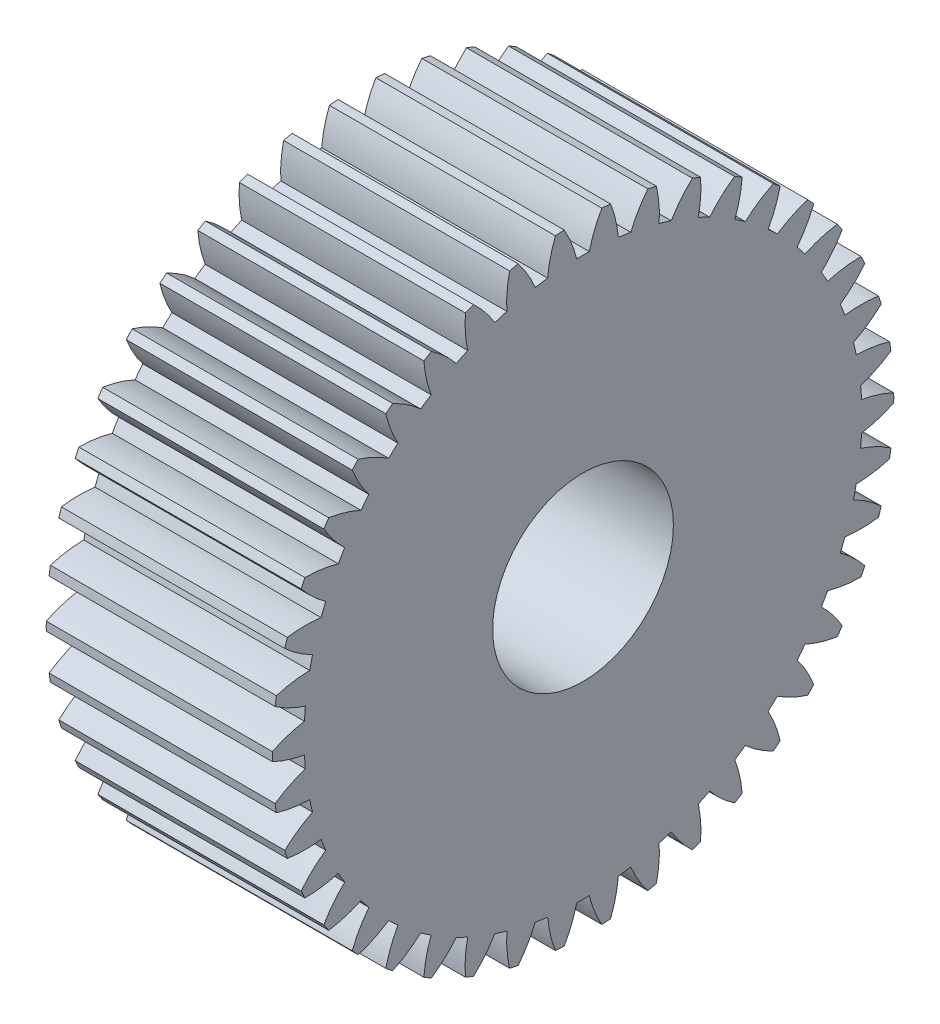
SolidWorks part; units mm, degrees
ref_plane "Plane1" through (0, 0, 0) normal (0, 0, 1) x (1, 0, 0)
ref_plane "Plane2" through (0, 0, 0) normal (0, 1, 0) x (1, 0, 0)
ref_plane "Plane3" through (0, 0, 0) normal (1, 0, 0) x (0, 0, -1)
sketch "HoldingSke" plane through (0, 0, 0) normal (0, 1, 0) x (1, 0, 0)
  line L0 (0, 0) -> (1.4863, -1.3383)
  line L1 (-15, 0) -> (100, 0) construction
  line L2 (0, 0) -> (-2.1039, 2.3779)
  line L3 (0, 0) -> (-11.863, 4.5341)
  line L4 (0, 0) -> (6.4178, 5.7786)
  line L5 (0, 0) -> (-46.8476, -17.4728)
  line L6 (0, 0) -> (-6.6317, -4.4744)
  line L7 (-2.1039, 2.3779) -> (8.6586, 51.2059)
  line L8 (-76.2, 54.61) -> (-75.9, 54.61)
  line L9 (-71.009, 38.7566) -> (-53.1078, 45.2721)
  line L10 (-76.2, 71.12) -> (104.1128, 71.12)
  line L11 (0, 0) -> (-8, 0)
  line L12 (-76.2, 101.6) -> (-76.181, 101.6)
  line L13 (24.9733, 27.94) -> (52.9518, 28.4284)
  line L14 (24.9733, 27.94) -> (24.9743, 27.94)
  line L15 (24.9733, 27.94) -> (100.4006, 29.5858)
  line L16 (-63.627, -0.5) -> (-12.827, -0.5)
  circle A0 centre (0, 0) radius 1
  circle A1 centre (0, 0) radius 9.874
  circle A2 centre (0, 0) radius 37.5
  circle A3 centre (0, 0) radius 1
  dimension "MHD" = 19.748
  dimension "Hub_dia" = 75
  dimension "Bore" = 2
  dimension "MBD" = 2
  dimension "Num_teeth" = 42
  dimension "Pitch" = 2
  dimension "Overall_len" = 50
  dimension "Show_teeth" = 42
  dimension "Thickness" = 8
  dimension "OAL" = 50.0001
  dimension "T_dim" = 0.3
  dimension "Ap" = 20
  dimension "H" = 19.05
  dimension "Pitch_radius" = 180.3128
  dimension "Width" = 8
  dimension "Backlash" = 0.019
  dimension "Addendum_fac" = 1
  dimension "Dedendum_fac" = 1.25
  dimension "Clearance_fac" = 0.25
  dimension "Dedendum_add" = 0.001
  dimension "Module" = 0.5
sketch "BasProSke" plane through (0, 0, 0) normal (0, 1, 0) x (1, 0, 0)
  line L0 (-10, 0) -> (60, 0) construction
  line L1 (0, 0) -> (0, 11)
  line L2 (0, 0) -> (8, 0)
  line L3 (8, 0) -> (8, 11)
  line L4 (8, 11) -> (0, 11)
  dimension "Thickness" = 8
  dimension "Diameter" = 22
revolve "Base-Revolve" add sketch "BasProSke" angle 360 about L0
sketch "TooCutSke" plane through (0, 0, 0) normal (1, 0, 0) x (0, 0, -1)
  line L1 (0, 0) -> (0, 107) construction
  line L2 (0, 0) -> (-0.4259, 10.4914) construction
  line L3 (0, 0) -> (-1.5684, 20.929) construction
  line L4 (-0.4259, 10.4914) -> (-0.7842, 10.4645) construction
  arc A0 (0.2229, 9.8715) -> (-0.2229, 9.8715) centre (0, 0) ccw
  arc A1 (0.6815, 11.0043) -> (-0.6815, 11.0043) centre (0, 0) ccw
  circle A2 centre (0, 0) radius 10.5 construction
  circle A3 centre (0, 0) radius 9.8668 construction
  arc A4 (-0.2229, 9.8715) -> (-0.6815, 11.0043) centre (-4.3039, 8.8786) ccw
  arc A5 (0.6815, 11.0043) -> (0.2229, 9.8715) centre (4.3039, 8.8786) ccw
  dimension "Root_dia" = 19.748
  dimension "Overcut_dia" = 22.0508
  dimension "Pitch_dia" = 21
  dimension "Base_dia" = 19.7335
  dimension "Flank_rad" = 4.2
  dimension "Half_ang" = 4.286
  dimension "Half_CT" = 0.3594
extrude "ToothCut" cut sketch "TooCutSke" along normal through all
fillet "Breaks" [suppressed] radius 0.01
fillet "RootFillets" [suppressed] radius 0.126
pattern_circular "TeethCuts" count 42 every 8.571 about axis through (-10, 0, 0) along (1, 0, 0) of "ToothCut", "RootFillets", "Breaks"
sketch "HubNeaOneSke" plane through (0, 0, 0) normal (-1, 0, 0) x (0, 0, 1)
  circle A0 centre (0, 0) radius 9.874
  dimension "Diameter" = 19.748
extrude "HubNearOne" [suppressed] add sketch "HubNeaOneSke" along normal blind 42.0001
sketch "HubNeaBotSke" plane through (0, 0, 0) normal (-1, 0, 0) x (0, 0, 1)
  circle A0 centre (0, 0) radius 9.874
  dimension "Diameter" = 19.748
extrude "HubNearBoth" [suppressed] add sketch "HubNeaBotSke" along normal blind 21
ref_plane "FarPln" through (8, 0, 0) normal (1, 0, 0) x (0, 0, -1)
sketch "HubFarSke" plane through (8, 0, 0) normal (1, 0, 0) x (0, 0, -1)
  circle A0 centre (0, 0) radius 9.874
  dimension "Diameter" = 19.748
extrude "HubFar" [suppressed] add sketch "HubFarSke" along normal blind 21
sketch "BorSke" plane through (0, 0, 0) normal (1, 0, 0) x (0, 0, -1)
  circle A0 centre (0, 0) radius 1
  dimension "Diameter" = 2
extrude "Bore" cut sketch "BorSke" along normal mid plane 100.0001
sketch "KeySke" plane through (0, 0, 0) normal (1, 0, 0) x (0, 0, -1)
  line L0 (-0.4, 0) -> (-0.4, 1.3)
  line L1 (-0.4, 1.3) -> (0.4, 1.3)
  line L2 (0.4, 1.3) -> (0.4, 0)
  line L3 (0, 0) -> (0, 34) construction
  line L4 (-0.4, 0) -> (0.4, 0)
  dimension "Offset" = 1.3
extrude "Keyway" [suppressed] cut sketch "KeySke" along normal mid plane 100.0001
pattern_circular "Keyway2" [suppressed] count 2 every 90 about axis through (-10, 0, 0) along (1, 0, 0)
sketch "Sketch1" plane through (8, 0, 0) normal (1, 0, 0) x (0, 0, -1)
  circle A0 centre (0, 0) radius 3.2
  dimension "D1" = 6.4
extrude "Cut-Extrude1" cut sketch "Sketch1" against normal through all
sketch "Sketch2" plane through (0, 0, 0) normal (-1, 0, 0) x (0, 0, 1)
  circle A0 centre (0, 0) radius 3.55
  dimension "D1" = 7.1
extrude "Cut-Extrude2" cut sketch "Sketch2" against normal blind 3.1
chamfer "Chamfer1" distance 0.5 angle 45 1 edges at (0, 0, 3.55)
equation "' \"Module@HoldingSke\" = 6.35"
equation "' \"Num_teeth@HoldingSke\" = 12"
equation "' \"Ap@HoldingSke\" =  20"
equation "' \"Ap@HoldingSke\" = 20"
equation "' \"Width@HoldingSke\" = 0.5 * 25.4"
equation "' \"Hub_dia@HoldingSke\"= 1 * 25.4"
equation "' \"Hub_dia@HoldingSke\" = 1 * 25.4"
equation "' \"Overall_len@HoldingSke\" = 1.0 * 25.4"
equation "' \"Bore@HoldingSke\" = 0.75 * 25.4"
equation "' \"T_dim@HoldingSke\" = 0.1 * 25.4"
equation "' \"Width@KeySke\" = 0.25 * 25.4"
equation "' \"Show_teeth@HoldingSke\" = 13"
equation "' \"Backlash@HoldingSke\" = 0.009 * 25.4"
equation "' \"Addendum_fac@HoldingSke\" = 1.0"
equation "' \"Dedendum_fac@HoldingSke\" = 1.25"
equation "' \"Dedendum_add@HoldingSke\" = 0.00005 * 25.4"
equation "' \"Clearance_fac@HoldingSke\" = 0.25"
equation "\"Pitch@HoldingSke\" = 1 / \"Module@HoldingSke\""
equation "\"Overcut_dia@TooCutSke\" = (\"Num_teeth@HoldingSke\" + 2 * \"Addendum_fac@HoldingSke\") / \"Pitch@HoldingSke\" + 0.002 * 25.4"
equation "\"Pitch_dia@TooCutSke\" = \"Num_teeth@HoldingSke\" / \"Pitch@HoldingSke\""
equation "\"Base_dia@TooCutSke\" = \"Num_teeth@HoldingSke\" / \"Pitch@HoldingSke\" * cos((\"Ap@HoldingSke\"  * 3.14159265 / 180))"
equation "\"Root_dia@TooCutSke\" = (\"Num_teeth@HoldingSke\" + 2) / \"Pitch@HoldingSke\" - 2 * (\"Addendum_fac@HoldingSke\" + \"Dedendum_fac@HoldingSke\") / \"Pitch@HoldingSke\" - \"Dedendum_add@HoldingSke\" * 2"
equation "\"Half_ang@TooCutSke\" = 180 / \"Num_teeth@HoldingSke\""
equation "\"Half_CT@TooCutSke\" = \"Num_teeth@HoldingSke\" / \"Pitch@HoldingSke\" * sin((3.14159265 / 2 / \"Num_teeth@HoldingSke\")) / 2 - 7 * \"Backlash@HoldingSke\" / 4"
equation "\"Flank_rad@TooCutSke\" = \"Num_teeth@HoldingSke\" / \"Pitch@HoldingSke\" / 5"
equation "\"Radius@RootFillets\" = \"Clearance_fac@HoldingSke\" / \"Pitch@HoldingSke\" + \"Dedendum_add@HoldingSke\""
equation "\"Break_rad@Breaks\" = 0.02 / \"Pitch@HoldingSke\""
equation "\"Thickness@HoldingSke\" = \"Width@HoldingSke\""
equation "\"OAL@HoldingSke\" = \"Thickness@HoldingSke\""
equation "\"MHD@HoldingSke\" = (\"Num_teeth@HoldingSke\" + 2) / \"Pitch@HoldingSke\" - 2 * (\"Addendum_fac@HoldingSke\" + \"Dedendum_fac@HoldingSke\")  / \"Pitch@HoldingSke\" - \"Dedendum_add@HoldingSke\" * 2"
equation "\"MBD@HoldingSke\" = (\"Num_teeth@HoldingSke\" + 2) / \"Pitch@HoldingSke\" - 2 * (\"Addendum_fac@HoldingSke\" + \"Dedendum_fac@HoldingSke\")  / \"Pitch@HoldingSke\" - \"Dedendum_add@HoldingSke\" * 2 - 0.002 * 25.4"
equation "\"MHD@HoldingSke\" = ((sgn( \"MHD@HoldingSke\" - \"Hub_dia@HoldingSke\" )-1)*( \"MHD@HoldingSke\" - \"Hub_dia@HoldingSke\" ))/-2+ \"Hub_dia@HoldingSke\""
equation "\"MBD@HoldingSke\" = ((sgn( \"MBD@HoldingSke\" - \"Bore@HoldingSke\" )-1)*( \"MBD@HoldingSke\" - \"Bore@HoldingSke\" ))/-2+ \"Bore@HoldingSke\""
equation "\"OAL@HoldingSke\" = ((sgn( \"OAL@HoldingSke\" - \"Overall_len@HoldingSke\" )+1)*( \"OAL@HoldingSke\" - \"Overall_len@HoldingSke\" ))/2 + \"Overall_len@HoldingSke\" + 0.000002 * 25.4"
equation "\"Num_teeth@TeethCuts\" = int( \"Show_teeth@HoldingSke\" ) + 1"
equation "\"Num_teeth@TeethCuts\" = ((sgn( \"Num_teeth@TeethCuts\" - \"Num_teeth@HoldingSke\" )-1)*( \"Num_teeth@TeethCuts\" - \"Num_teeth@HoldingSke\" ))/-2+ \"Num_teeth@HoldingSke\""
equation "\"Num_teeth@TeethCuts\" = ((sgn( \"Num_teeth@TeethCuts\" - 2.0)+1)*( \"Num_teeth@TeethCuts\" - 2.0))/2 +2.0"
equation "\"Angle@TeethCuts\" = 360.0 / \"Num_teeth@HoldingSke\""
equation "\"Diameter@BasProSke\" = (\"Num_teeth@HoldingSke\" + 2 * \"Addendum_fac@HoldingSke\") / \"Pitch@HoldingSke\""
equation "\"Thickness@BasProSke\"  = \"Thickness@HoldingSke\""
equation "' \"Fillet_rad@BasProSke\" =  \"Thickness@HoldingSke\" * 0.05"
equation "' \"Fillet_rad@BasProSke\" = \"Thickness@HoldingSke\" * 0.05"
equation "\"MHD@HoldingSke\" = ((sgn( \"MHD@HoldingSke\" - \"Root_dia@TooCutSke\" )-1)*( \"MHD@HoldingSke\" - \"Root_dia@TooCutSke\" ))/-2+ \"Root_dia@TooCutSke\""
equation "\"Diameter@HubNeaOneSke\" = \"MHD@HoldingSke\""
equation "\"Length@HubNearOne\" = \"OAL@HoldingSke\" - \"Thickness@BasProSke\""
equation "\"Diameter@HubNeaBotSke\" = \"MHD@HoldingSke\""
equation "\"Length@HubNearBoth\" = ( \"OAL@HoldingSke\" - \"Thickness@BasProSke\" ) / 2.0"
equation "\"Thickness@FarPln\" = \"Thickness@BasProSke\""
equation "\"Diameter@HubFarSke\" = \"MHD@HoldingSke\""
equation "\"Length@HubFar\" = ( \"OAL@HoldingSke\" - \"Thickness@BasProSke\" ) / 2.0"
equation "\"Diameter@BorSke\" = \"MBD@HoldingSke\""
equation "\"D1@Bore\" = \"OAL@HoldingSke\" * 2.0"
equation "\"D1@Keyway\" = \"OAL@HoldingSke\" * 2.0"
equation "\"Offset@KeySke\" = \"T_dim@HoldingSke\" + \"MBD@HoldingSke\" / 2.0"
